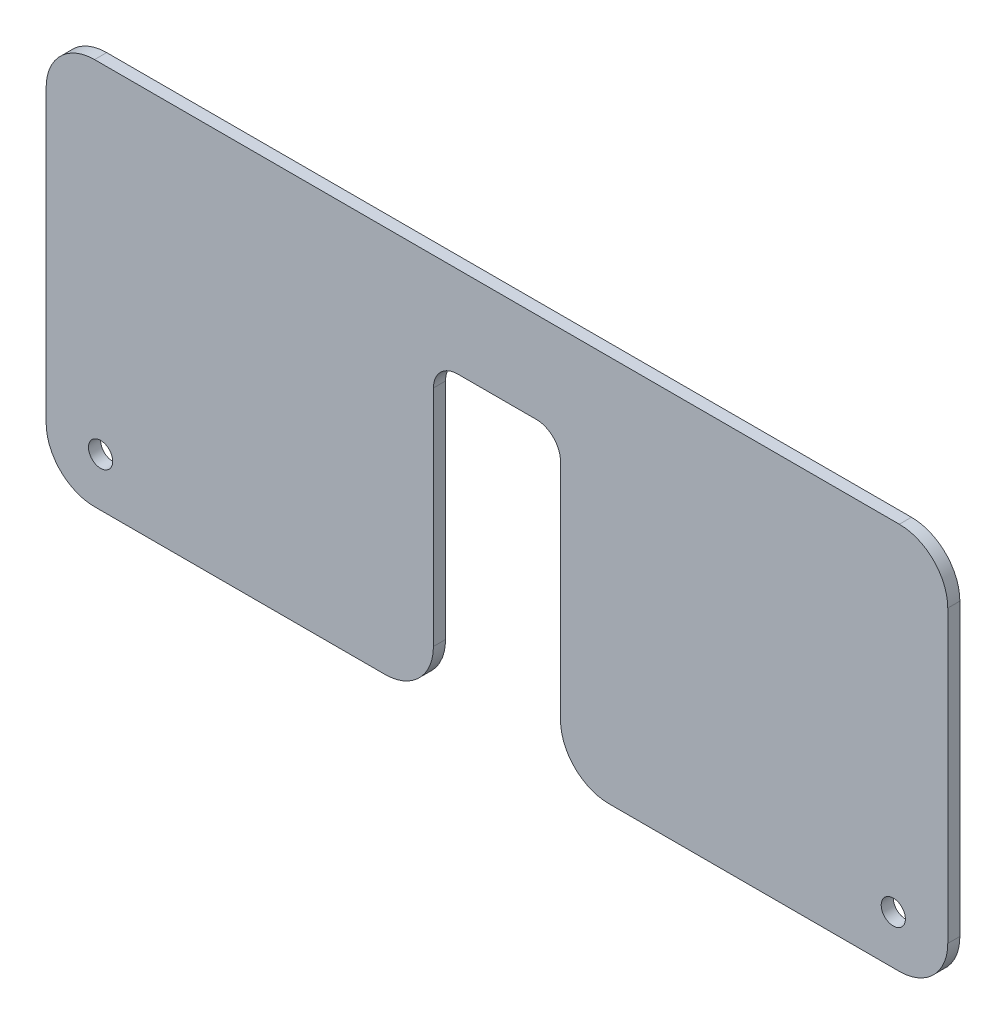
SolidWorks part; units mm, degrees
ref_plane "Спереди" through (0, 0, 0) normal (0, 0, 1) x (1, 0, 0)
ref_plane "Сверху" through (0, 0, 0) normal (0, 1, 0) x (1, 0, 0)
ref_plane "Справа" through (0, 0, 0) normal (1, 0, 0) x (0, 0, -1)
sketch "Sketch1" plane through (0, 0, 0) normal (0, 0, 1) x (1, 0, 0)
  line L0 (0, 0) -> (-66.5, 0)
  line L1 (-74.5, -8) -> (-74.5, -56)
  line L2 (-66.5, -64) -> (-18.5, -64)
  line L3 (-10.5, -56) -> (-10.5, -19)
  line L4 (-6.5, -15) -> (0, -15)
  line L5 (0, -15) -> (6.5, -15)
  line L6 (10.5, -19) -> (10.5, -56)
  line L7 (18.5, -64) -> (66.5, -64)
  line L8 (74.5, -56) -> (74.5, -8)
  line L9 (66.5, 0) -> (0, 0)
  line L10 (0, 12.9389) -> (0, -23.9078) construction
  line L11 (-65.5, -48.3041) -> (-65.5, -76.7383) construction
  line L12 (-81.9532, -56) -> (-49.0468, -56) construction
  circle A0 centre (-65.5, -56) radius 2
  circle A1 centre (65.5, -56) radius 2
  arc A2 (-18.5, -64) -> (-10.5, -56) centre (-18.5, -56) ccw
  arc A3 (10.5, -56) -> (18.5, -64) centre (18.5, -56) ccw
  arc A4 (66.5, -64) -> (74.5, -56) centre (66.5, -56) ccw
  arc A5 (74.5, -8) -> (66.5, 0) centre (66.5, -8) ccw
  arc A6 (-66.5, 0) -> (-74.5, -8) centre (-66.5, -8) ccw
  arc A7 (-74.5, -56) -> (-66.5, -64) centre (-66.5, -56) ccw
  arc A8 (6.5, -15) -> (10.5, -19) centre (6.5, -19) cw
  arc A9 (-10.5, -19) -> (-6.5, -15) centre (-6.5, -19) cw
  point P19 (0, 0)
  point P38 (0, 0)
  dimension "D6" = 4
  dimension "D7" = 8
  dimension "D8" = 4
  dimension "D1" = 64
  dimension "D2" = 21
  dimension "D3" = 149
  dimension "D4" = 8
  dimension "D5" = 9
  dimension "D9" = 15
extrude "Boss-Extrude1" add sketch "Sketch1" along normal blind 2
